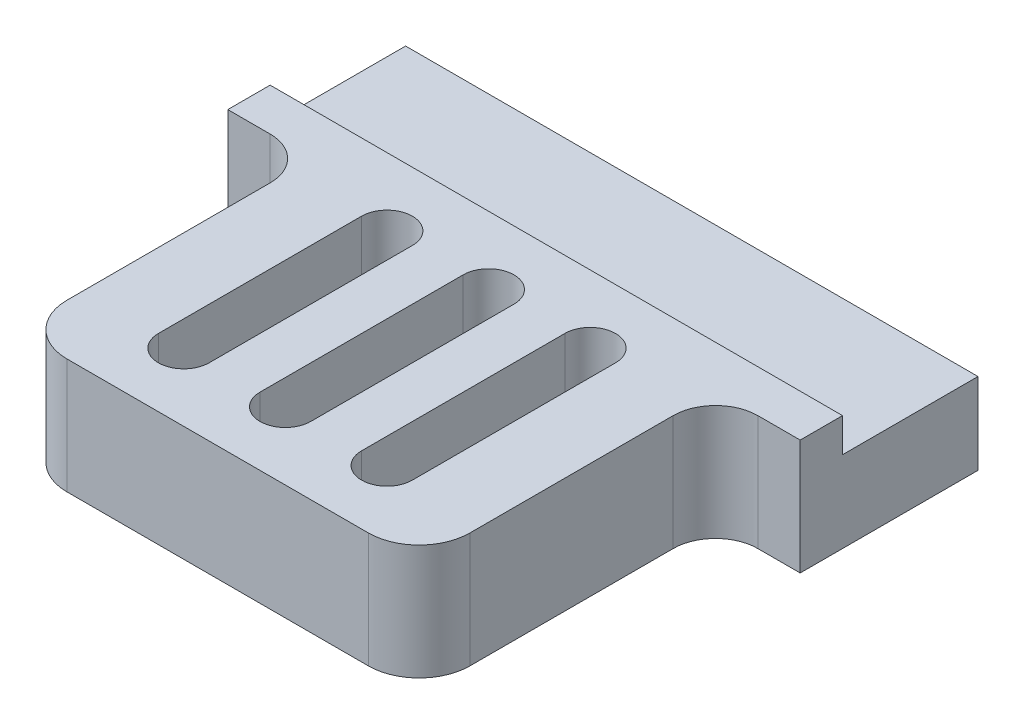
SolidWorks part; units mm, degrees
ref_plane "前基準面" through (0, 0, 0) normal (0, 0, 1) x (1, 0, 0)
ref_plane "上基準面" through (0, 0, 0) normal (0, 1, 0) x (1, 0, 0)
ref_plane "右基準面" through (0, 0, 0) normal (1, 0, 0) x (0, 0, -1)
sketch "草圖1" plane through (0, 0, 0) normal (0, 0, 1) x (1, 0, 0)
  line L1 (-16.9, 2.4) -> (16.9, 2.4)
  line L2 (-16.9, 2.4) -> (-16.9, -2.4)
  line L3 (-16.9, -2.4) -> (16.9, -2.4)
  line L4 (16.9, 2.4) -> (16.9, -2.4)
  point P4 (0, 2.4)
  point P6 (-16.9, 0)
  dimension "D1" = 4.8
  dimension "D2" = 33.8
extrude "填料-伸長1" add sketch "草圖1" along normal blind 28
sketch "草圖2" plane through (0, 0, 28) normal (0, 0, 1) x (1, 0, 0)
  line L1 (-16.9, 2.4) -> (16.9, 2.4)
  line L2 (-16.9, 2.4) -> (-16.9, 4.4)
  line L3 (-16.9, 4.4) -> (16.9, 4.4)
  line L4 (16.9, 2.4) -> (16.9, 4.4)
  line L7 (16.9, -2.4) -> (16.9, 2.4) construction
  dimension "D1" = 2
extrude "填料-伸長2" add sketch "草圖2" against normal blind 20
sketch "草圖3" plane through (0, 4.4, 0) normal (0, 1, 0) x (1, 0, 0)
  line L0 (0, -12) -> (0, -24) construction
  line L1 (1.5, -12) -> (1.5, -24)
  line L2 (-1.5, -12) -> (-1.5, -24)
  line L3 (16.9, -28) -> (-16.9, -28) construction
  line L4 (6, -12) -> (6, -24) construction
  line L5 (7.5, -12) -> (7.5, -24)
  line L6 (4.5, -12) -> (4.5, -24)
  line L10 (-6, -12) -> (-6, -24) construction
  line L11 (-4.5, -12) -> (-4.5, -24)
  line L12 (-7.5, -12) -> (-7.5, -24)
  line L43 (12, -12) -> (12, -24) construction
  line L44 (13.5, -12) -> (13.5, -24)
  line L45 (10.5, -12) -> (10.5, -24)
  line L46 (-12, -12) -> (-12, -24) construction
  line L47 (-10.5, -12) -> (-10.5, -24)
  line L48 (-13.5, -12) -> (-13.5, -24)
  line L49 (12, -12) -> (12, -24) construction
  line L50 (13.5, -12) -> (13.5, -24)
  line L51 (10.5, -12) -> (10.5, -24)
  line L52 (-12, -12) -> (-12, -24) construction
  line L53 (-10.5, -12) -> (-10.5, -24)
  line L54 (-13.5, -12) -> (-13.5, -24)
  arc A0 (1.5, -12) -> (-1.5, -12) centre (0, -12) ccw
  arc A1 (-1.5, -24) -> (1.5, -24) centre (0, -24) ccw
  arc A2 (7.5, -12) -> (4.5, -12) centre (6, -12) ccw
  arc A3 (4.5, -24) -> (7.5, -24) centre (6, -24) ccw
  arc A6 (-4.5, -12) -> (-7.5, -12) centre (-6, -12) ccw
  arc A7 (-7.5, -24) -> (-4.5, -24) centre (-6, -24) ccw
  arc A32 (13.5, -12) -> (10.5, -12) centre (12, -12) ccw
  arc A33 (10.5, -24) -> (13.5, -24) centre (12, -24) ccw
  arc A34 (-10.5, -12) -> (-13.5, -12) centre (-12, -12) ccw
  arc A35 (-13.5, -24) -> (-10.5, -24) centre (-12, -24) ccw
  point P3 (0, -18)
  point P13 (6, -18)
  point P27 (-6, -18)
  point P34 (12, -18)
  point P40 (-12, -18)
  point P47 (12, -18)
  point P54 (-12, -18)
  point P61 (12, -18)
  point P68 (-12, -18)
  point P75 (12, -18)
  point P82 (-12, -18)
  point P89 (12, -18)
  point P96 (-12, -18)
  point P103 (12, -18)
  point P110 (-12, -18)
  point P117 (12, -18)
  point P124 (-12, -18)
  dimension "D1" = 3
  dimension "D2" = 12
  dimension "D3" = 10
  dimension "D4" = 3
  dimension "D5" = 3
extrude "除料-伸長1" cut sketch "草圖3" against normal through all
sketch "草圖4" plane through (0, 4.4, 0) normal (0, 1, 0) x (1, 0, 0)
  line L0 (-16.9, -8) -> (-16.9, -28) construction
  line L1 (-16.9, -10.5) -> (-11.9, -10.5)
  line L2 (-16.9, -10.5) -> (-16.9, -28)
  line L3 (-16.9, -28) -> (-11.9, -28)
  line L4 (-11.9, -10.5) -> (-11.9, -28)
  line L5 (16.9, -28) -> (-16.9, -28) construction
  line L6 (-16.9, -8) -> (16.9, -8) construction
  line L7 (0, 0) -> (0, -28) construction
  line L8 (11.9, -10.5) -> (11.9, -28)
  line L9 (16.9, -28) -> (11.9, -28)
  line L10 (16.9, -10.5) -> (16.9, -28)
  line L11 (16.9, -10.5) -> (11.9, -10.5)
  dimension "D1" = 2.5
  dimension "D2" = 5
extrude "除料-伸長2" cut sketch "草圖4" against normal through all
fillet "圓角1" radius 3 2 edges at (11.9, 1, 28) (-11.9, 1, 28)
fillet "圓角3" radius 2.5 2 edges at (11.9, 1, 10.5) (-11.9, 1, 10.5)
